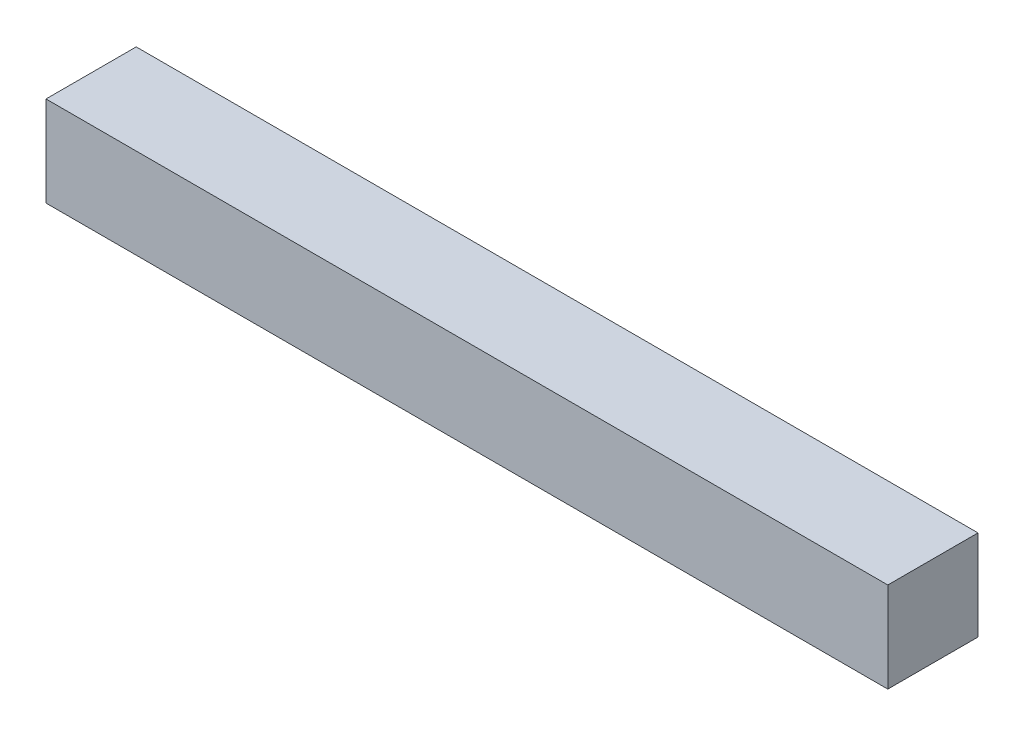
SolidWorks part; units mm, degrees
ref_plane "Ebene vorne" through (0, 0, 0) normal (0, 0, 1) x (1, 0, 0)
ref_plane "Ebene oben" through (0, 0, 0) normal (0, 1, 0) x (1, 0, 0)
ref_plane "Ebene rechts" through (0, 0, 0) normal (1, 0, 0) x (0, 0, -1)
sketch "Skizze1" plane through (0, 0, 0) normal (0, 0, 1) x (1, 0, 0)
  line L1 (-140, 15) -> (140, 15)
  line L2 (-140, 15) -> (-140, -15)
  line L3 (-140, -15) -> (140, -15)
  line L4 (140, 15) -> (140, -15)
  line L5 (-140, 15) -> (140, -15) construction
  line L6 (-140, -15) -> (140, 15) construction
  point P0 (0, 0)
  dimension "D1" = 280
  dimension "D2" = 30
extrude "Aufsatz-Linear austragen1" add sketch "Skizze1" along normal blind 30
